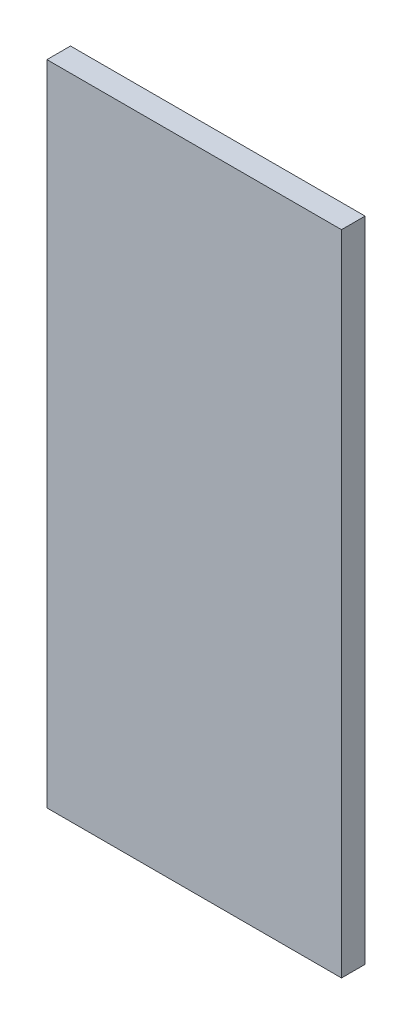
SolidWorks part; units mm, degrees
ref_plane "Front Plane" through (0, 0, 0) normal (0, 0, 1) x (1, 0, 0)
ref_plane "Top Plane" through (0, 0, 0) normal (0, 1, 0) x (1, 0, 0)
ref_plane "Right Plane" through (0, 0, 0) normal (1, 0, 0) x (0, 0, -1)
sketch "Sketch2" plane through (0, 0, 0) normal (0, 0, 1) x (1, 0, 0)
  line L1 (12.5, -27.5) -> (-12.5, -27.5)
  line L2 (12.5, -27.5) -> (12.5, 27.5)
  line L3 (12.5, 27.5) -> (-12.5, 27.5)
  line L4 (-12.5, -27.5) -> (-12.5, 27.5)
  line L5 (12.5, -27.5) -> (-12.5, 27.5) construction
  line L6 (12.5, 27.5) -> (-12.5, -27.5) construction
  point P0 (0, 0)
  dimension "D1" = 25
  dimension "D2" = 55
extrude "Boss-Extrude1" add sketch "Sketch2" along normal blind 2
